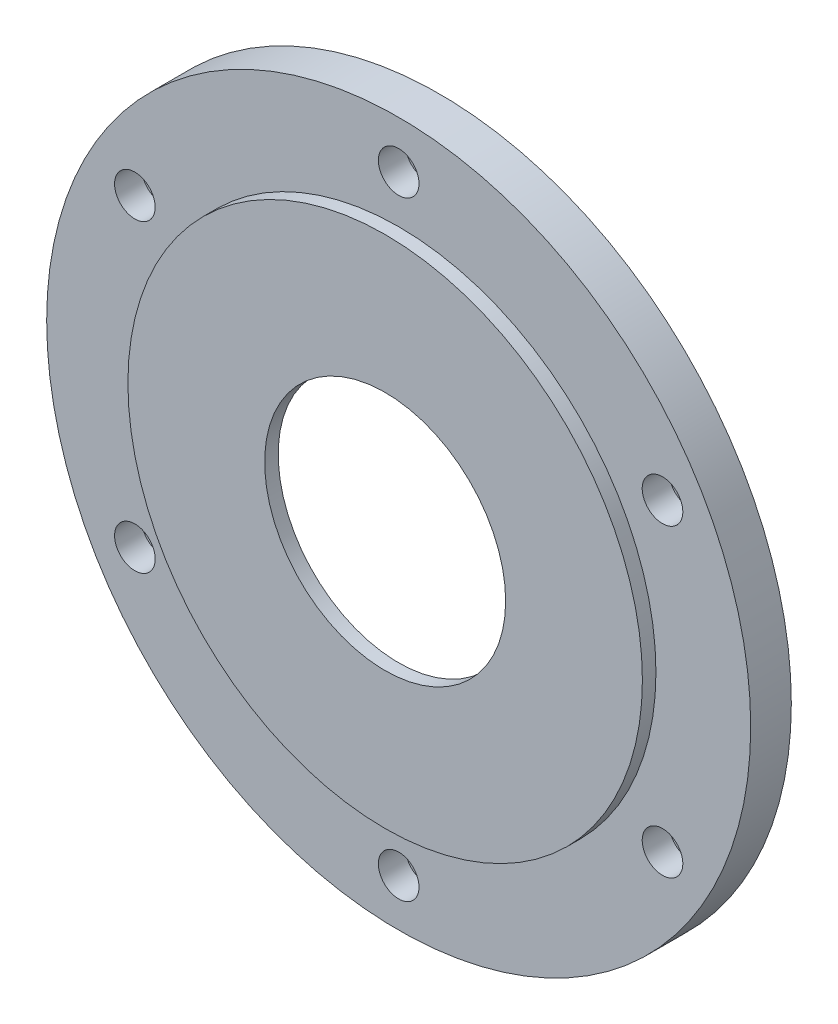
SolidWorks part; units mm, degrees
material "Resina de melamina"
ref_plane "Alzado" through (0, 0, 0) normal (0, 0, 1) x (1, 0, 0)
ref_plane "Planta" through (0, 0, 0) normal (0, 1, 0) x (1, 0, 0)
ref_plane "Vista lateral" through (0, 0, 0) normal (1, 0, 0) x (0, 0, -1)
sketch "Croquis1" plane through (0, 0, 0) normal (0, 0, 1) x (1, 0, 0)
  circle A0 centre (0, 0) radius 8.9
  circle A1 centre (0, 0) radius 19
  dimension "D1" = 17.8
  dimension "D2" = 38
extrude "Saliente-Extruir1" add sketch "Croquis1" along normal blind 1
sketch "Croquis2" plane through (0, 0, 0) normal (0, 0, -1) x (-1, 0, 0)
  circle A0 centre (0, 0) radius 19
  circle A1 centre (0, 0) radius 26
  dimension "D1" = 52
extrude "Saliente-Extruir2" add sketch "Croquis2" along normal blind 3 separate body
sketch "Croquis3" plane through (0, 0, 0) normal (0, 0, 1) x (1, 0, 0)
  line L0 (0, 0) -> (0, 22.5) construction
  line L1 (0, 22.5) -> (0, 26) construction
  line L2 (0, 22.5) -> (0, 18.876) construction
  circle A0 centre (0, 22.5) radius 1.5
  circle A1 centre (0, 0) radius 26 construction
  circle A2 centre (19.4856, 11.25) radius 1.5
  circle A3 centre (19.4856, -11.25) radius 1.5
  circle A4 centre (0, -22.5) radius 1.5
  circle A5 centre (-19.4856, -11.25) radius 1.5
  circle A6 centre (-19.4856, 11.25) radius 1.5
  dimension "D3" = 3
  dimension "D1" = 22.5
  dimension "D2" = 6
extrude "Cortar-Extruir1" cut sketch "Croquis3" against normal blind 2
